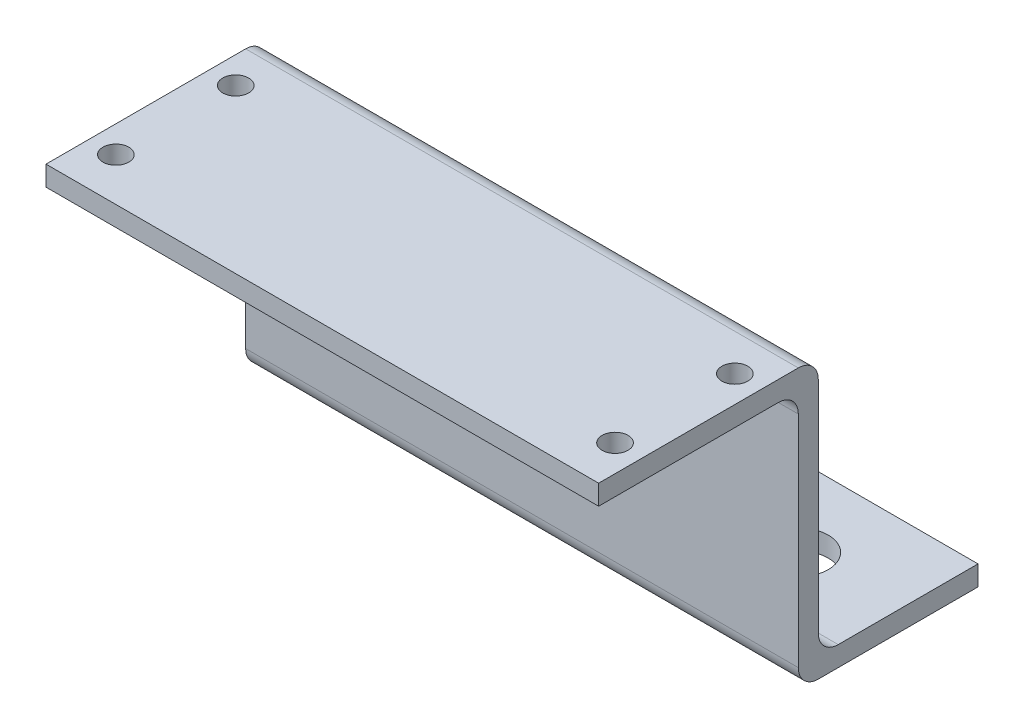
SolidWorks part; units mm, degrees
ref_plane "前视基准面" through (0, 0, 0) normal (0, 0, 1) x (1, 0, 0)
ref_plane "上视基准面" through (0, 0, 0) normal (0, 1, 0) x (1, 0, 0)
ref_plane "右视基准面" through (0, 0, 0) normal (1, 0, 0) x (0, 0, -1)
other "Configuration Table"
sketch "草图1" plane through (0, 0, 0) normal (0, 1, 0) x (1, 0, 0)
  line L0 (2121.3203, -2121.3203) -> (-103944.6968, 103944.6968) construction
  line L1 (-2121.3203, -2121.3203) -> (103944.6968, 103944.6968) construction
  line L2 (-17.6777, 17.6777) -> (17.6777, 17.6777) construction
  line L5 (0, -1000) -> (0, 49000) construction
  line L10 (17.6777, 17.6777) -> (17.6777, 25.6777) construction
  line L11 (-17.6777, 9.6777) -> (-27.6777, 9.6777)
  line L12 (-27.6777, 9.6777) -> (-27.6777, 25.6777)
  line L13 (27.6777, 25.6777) -> (27.6777, 9.6777)
  line L14 (17.6777, 25.6777) -> (27.6777, 25.6777)
  line L15 (27.6777, 9.6777) -> (-17.6777, 9.6777)
  line L16 (-27.6777, 25.6777) -> (17.6777, 25.6777)
  circle A0 centre (0, 0) radius 25 construction
  circle A3 centre (-17.6777, 17.6777) radius 3
  circle A4 centre (17.6777, 17.6777) radius 3
  dimension "D1" = 8
  dimension "D4" = 16
  dimension "D5" = 16
  dimension "D2" = 10
  dimension "D3" = 10
  dimension "D6" = 50
  dimension "D7" = 55.3553
extrude "凸台-拉伸1" add sketch "草图1" along normal blind 2
ref_plane "基准面1" through (0, 0, -9.6777) normal (0, 0, 1) x (1, 0, 0)
sketch "草图2" plane through (0, 0, -9.6777) normal (0, 0, 1) x (1, 0, 0)
  line L0 (-27.6777, 2) -> (-27.6777, 0) construction
  line L1 (-27.6777, 2) -> (0, 2)
  line L2 (-27.6777, 2) -> (-27.6777, 0)
  line L3 (-27.6777, 0) -> (0, 0)
  line L4 (0, 2) -> (0, 0)
  line L5 (27.6777, 2) -> (27.6777, 0) construction
  line L6 (0, 2) -> (27.6777, 2)
  line L7 (0, 2) -> (0, 0)
  line L8 (0, 0) -> (27.6777, 0)
  line L9 (27.6777, 2) -> (27.6777, 0)
  line L10 (-27.6777, 2) -> (-27.6777, 26)
  line L11 (-27.6777, 26) -> (27.6777, 26)
  line L12 (27.6777, 26) -> (27.6777, 2)
  line L13 (0, 2) -> (0, 26) construction
  line L14 (0, 14) -> (-27.6777, 14) construction
  line L15 (0, 14) -> (-9, 14)
  circle A0 centre (-9, 14) radius 4
  circle A1 centre (9, 14) radius 4
  dimension "D3" = 12
  dimension "D1" = 24
  dimension "D2" = 9
extrude "凸台-拉伸2" add sketch "草图2" against normal blind 2
ref_plane "基准面2" through (0, 0, -9.6777) normal (0, 0, 1) x (1, 0, 0)
sketch "草图3" plane through (0, 0, -9.6777) normal (0, 0, 1) x (1, 0, 0)
  line L1 (-27.6777, 26) -> (27.6777, 26)
  line L2 (-27.6777, 26) -> (-27.6777, 0)
  line L3 (-27.6777, 0) -> (27.6777, 0)
  line L4 (27.6777, 26) -> (27.6777, 0)
  circle A0 centre (-9, 14) radius 4
  circle A1 centre (9, 14) radius 4
extrude "凸台-拉伸3" add sketch "草图3" along normal blind 2
ref_plane "基准面3" through (0, 0, -9.6777) normal (0, 0, 1) x (1, 0, 0)
sketch "草图4" plane through (0, 0, -9.6777) normal (0, 0, 1) x (1, 0, 0)
  line L0 (-27.6777, 26) -> (27.6777, 26)
  line L1 (27.6777, 26) -> (27.6777, 2)
  line L2 (27.6777, 0) -> (27.6777, 26) construction
  line L3 (27.6777, 2) -> (-27.6777, 2)
  line L4 (-27.6777, 2) -> (-27.6777, 26)
extrude "切除-拉伸1" cut sketch "草图4" against normal blind 2
fillet "圆角1" radius 2 1 edges at (0, 0, -7.6777)
ref_plane "基准面5" through (0, 0, -9.6777) normal (0, 0, -1) x (-1, 0, 0)
sketch "草图5" plane through (0, 0, -9.6777) normal (0, 0, -1) x (-1, 0, 0)
  line L0 (-27.6777, 26) -> (-27.6777, 28)
  line L1 (27.6777, 26) -> (27.6777, 28)
  line L2 (-27.6777, 26) -> (27.6777, 26) construction
  line L3 (27.6777, 28) -> (-27.6777, 28)
  line L4 (-27.6777, 26) -> (27.6777, 26)
extrude "凸台-拉伸4" add sketch "草图5" against normal blind 22
sketch "草图6" plane through (0, 28, 0) normal (0, 1, 0) x (1, 0, 0)
  line L0 (0, 0) -> (-50000, 0) construction
  line L1 (0, 0) -> (0, -50000) construction
  line L2 (0.3962, 0) -> (25, 0) construction
  line L3 (25, 0) -> (25, -50000) construction
  line L4 (25, 0) -> (25, -8) construction
  line L5 (25, 0) -> (25, 4) construction
  circle A0 centre (25, -8) radius 1.3
  circle A1 centre (25, 4) radius 1.3
  circle A2 centre (-25, 4) radius 1.3
  circle A3 centre (-25, -8) radius 1.3
  dimension "D1" = 4
  dimension "D2" = 8
  dimension "D3" = 25
extrude "切除-拉伸2" cut sketch "草图6" against normal blind 22
fillet "圆角2" radius 2 1 edges at (0, 28, -9.6777)
fillet "圆角3" radius 2 1 edges at (0, 26, -7.6777)
fillet "圆角4" radius 2 1 edges at (0, 2, -9.6777)
sketch "草图7" plane through (0, 28, 0) normal (0, 1, 0) x (1, 0, 0)
  line L0 (-25, 4) -> (-25, -8) construction
